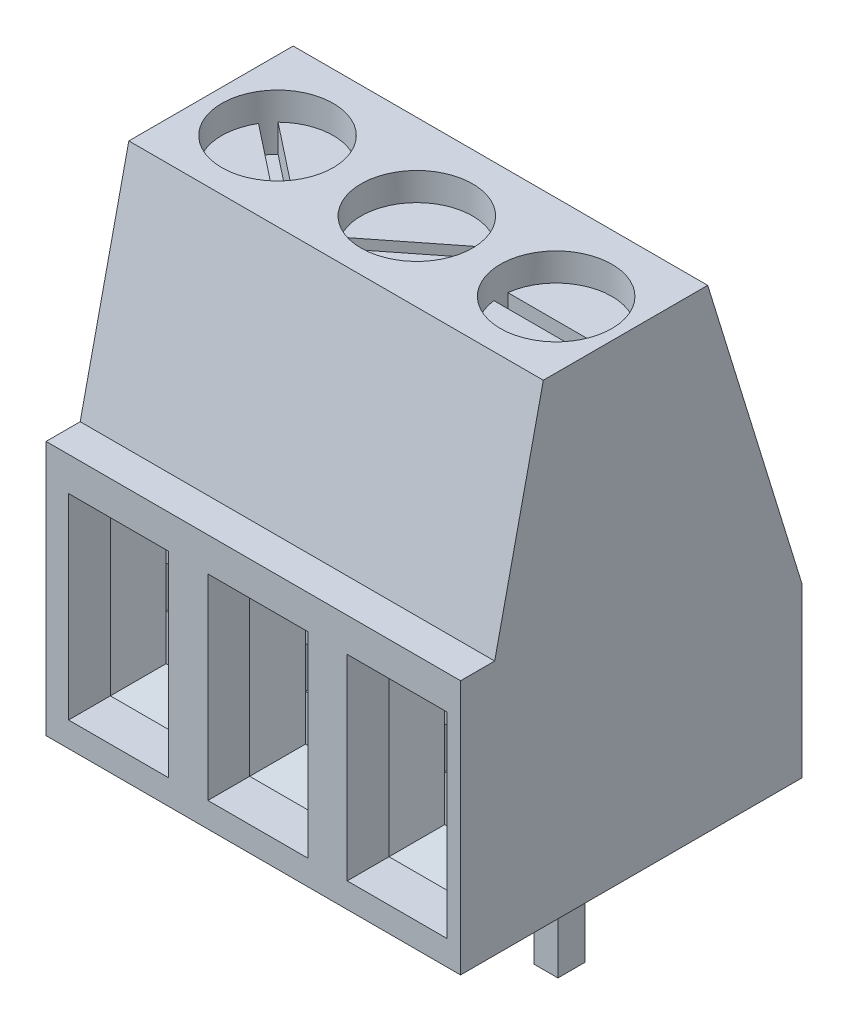
SolidWorks part; units mm, degrees
ref_plane "Front Plane" through (0, 0, 0) normal (0, 0, 1) x (1, 0, 0)
ref_plane "Top Plane" through (0, 0, 0) normal (0, 1, 0) x (1, 0, 0)
ref_plane "Right Plane" through (0, 0, 0) normal (1, 0, 0) x (0, 0, -1)
sketch "Sketch1" plane through (0, 0, 0) normal (0, 1, 0) x (1, 0, 0)
  line L1 (0, 0) -> (20.701, 0)
  line L2 (0, 0) -> (0, 6.223)
  line L3 (0, 6.223) -> (20.701, 6.223)
  line L4 (20.701, 0) -> (20.701, 6.223)
  dimension "D1" = 20.701
  dimension "D2" = 6.223
extrude "Extrude1" add sketch "Sketch1" along normal blind 8.636
sketch "Sketch2" plane through (20.701, 0, 0) normal (1, 0, 0) x (0, 0, -1)
  line L0 (-2.8691, 4.6459) -> (0.6218, 4.6459)
  line L1 (0.6218, 4.6459) -> (2.2176, 11.8272)
  line L2 (2.2176, 11.8272) -> (-2.8691, 11.8272)
  line L3 (-2.8691, 11.8272) -> (-2.8691, 4.6459)
extrude "Cut-Extrude1" cut sketch "Sketch2" against normal blind 25.4
sketch "Sketch3" plane through (20.701, 0, 0) normal (1, 0, 0) x (0, 0, -1)
  line L0 (4.013, 10.2314) -> (6.9054, 0.8558)
  line L1 (6.9054, 0.8558) -> (9.1994, 0.8558)
  line L2 (9.1994, 0.8558) -> (9.1994, 10.2314)
  line L3 (9.1994, 10.2314) -> (4.013, 10.2314)
extrude "Cut-Extrude2" cut sketch "Sketch3" against normal blind 25.4
sketch "Sketch4" plane through (0, 8.636, 0) normal (0, 1, 0) x (1, 0, 0)
  line L0 (0, 4.5051) -> (0, 1.5085) construction
  circle A0 centre (1.27, 2.9491) radius 1.016
  circle A1 centre (3.81, 2.9491) radius 1.016
  circle A2 centre (6.35, 2.9491) radius 1.016
  circle A3 centre (8.89, 2.9491) radius 1.016
  circle A4 centre (11.43, 2.9491) radius 1.016
  circle A5 centre (13.97, 2.9491) radius 1.016
  circle A6 centre (16.51, 2.9491) radius 1.016
  circle A7 centre (19.05, 2.9491) radius 1.016
  dimension "D1" = 1.27
extrude "Cut-Extrude3" cut sketch "Sketch4" against normal blind 0.508
sketch "Sketch5" plane through (0, 8.128, 0) normal (0, 1, 0) x (1, 0, 0)
  line L8 (18.1734, 3.4782) -> (19.7694, 2.2205)
  line L9 (16.7061, 3.9541) -> (16.0726, 2.0233)
  line L10 (12.9692, 3.1653) -> (14.8868, 2.4932)
  line L11 (11.303, 3.9651) -> (11.303, 1.9331)
  line L12 (8.6939, 1.9441) -> (9.3274, 3.8749)
  line L13 (5.334, 2.8221) -> (7.366, 2.8221)
  line L14 (3.0906, 2.2205) -> (4.6866, 3.4782)
  line L15 (0.3934, 3.4782) -> (1.9894, 2.2205)
  line L16 (18.3306, 3.6777) -> (19.9266, 2.42)
  line L17 (16.9474, 3.8749) -> (16.3139, 1.9441)
  line L18 (13.0532, 3.405) -> (14.9708, 2.7329)
  line L19 (11.557, 3.9651) -> (11.557, 1.9331)
  line L20 (8.4526, 2.0233) -> (9.0861, 3.9541)
  line L21 (5.334, 3.0761) -> (7.366, 3.0761)
  line L22 (2.9334, 2.42) -> (4.5294, 3.6777)
  line L23 (0.5506, 3.6777) -> (2.1466, 2.42)
  circle A13 centre (1.27, 2.9491) radius 1.016
  circle A14 centre (3.81, 2.9491) radius 1.016
  circle A15 centre (6.35, 2.9491) radius 1.016
  circle A16 centre (8.89, 2.9491) radius 1.005
  circle A17 centre (11.43, 2.9491) radius 1.016
  circle A18 centre (13.97, 2.9491) radius 1.016
  circle A19 centre (16.51, 2.9491) radius 1.016
  circle A20 centre (19.05, 2.9491) radius 0.9996
  circle M1 centre (1.27, 2.9491) radius 1.016
extrude "Cut-Extrude4" cut sketch "Sketch5" against normal blind 0.508 contours L23 L15 M1 | L14 A14 L22 | L13 A15 L21 | L12 A16 L20 | L19 A17 L11 | L10 A18 L18 | L17 A19 L9 | L8 A20 L16
sketch "Sketch6" plane through (0, 0, 0) normal (0, 0, 1) x (1, 0, 0)
  line L0 (2.9501, 4.0288) -> (2.9501, 0.4524)
  line L1 (0.4101, 4.0288) -> (2.232, 4.0288)
  line L2 (0.4101, 4.0288) -> (0.4101, 0.4524)
  line L3 (0.4101, 0.4524) -> (2.232, 0.4524)
  line L4 (2.232, 4.0288) -> (2.232, 0.4524)
  line L5 (2.9501, 4.0288) -> (4.772, 4.0288)
  line L6 (4.772, 4.0288) -> (4.772, 0.4524)
  line L7 (2.9501, 0.4524) -> (4.772, 0.4524)
  line L8 (5.4901, 4.0288) -> (5.4901, 0.4524)
  line L9 (5.4901, 4.0288) -> (7.312, 4.0288)
  line L10 (7.312, 4.0288) -> (7.312, 0.4524)
  line L11 (5.4901, 0.4524) -> (7.312, 0.4524)
  line L12 (8.0301, 4.0288) -> (8.0301, 0.4524)
  line L13 (8.0301, 4.0288) -> (9.852, 4.0288)
  line L14 (9.852, 4.0288) -> (9.852, 0.4524)
  line L15 (8.0301, 0.4524) -> (9.852, 0.4524)
  line L16 (10.5701, 4.0288) -> (10.5701, 0.4524)
  line L17 (10.5701, 4.0288) -> (12.392, 4.0288)
  line L18 (12.392, 4.0288) -> (12.392, 0.4524)
  line L19 (10.5701, 0.4524) -> (12.392, 0.4524)
  line L20 (13.1101, 4.0288) -> (13.1101, 0.4524)
  line L21 (13.1101, 4.0288) -> (14.932, 4.0288)
  line L22 (14.932, 4.0288) -> (14.932, 0.4524)
  line L23 (13.1101, 0.4524) -> (14.932, 0.4524)
  line L24 (15.6501, 4.0288) -> (15.6501, 0.4524)
  line L25 (15.6501, 4.0288) -> (17.472, 4.0288)
  line L26 (17.472, 4.0288) -> (17.472, 0.4524)
  line L27 (15.6501, 0.4524) -> (17.472, 0.4524)
  line L28 (18.1901, 4.0288) -> (18.1901, 0.4524)
  line L29 (18.1901, 4.0288) -> (20.012, 4.0288)
  line L30 (20.012, 4.0288) -> (20.012, 0.4524)
  line L31 (18.1901, 0.4524) -> (20.012, 0.4524)
extrude "Cut-Extrude5" cut sketch "Sketch6" against normal blind 1.27
chamfer "Chamfer1" distance 0.508 angle 45 11 edges at (7.312, 2.2406, -1.27) (5.4901, 2.2406, -1.27) (6.4011, 4.0288, -1.27) (4.772, 2.2406, -1.27) (3.8611, 0.4524, -1.27) (2.9501, 2.2406, -1.27) (3.8611, 4.0288, -1.27) (1.3211, 4.0288, -1.27) (2.232, 2.2406, -1.27) (1.3211, 0.4524, -1.27) (0.4101, 2.2406, -1.27)
sketch "Sketch7" plane through (0, 0, -1.27) normal (0, 0, 1) x (1, 0, 0)
  line L0 (0.9181, 3.5208) -> (0.9181, 0.9604) construction
  line L1 (0.9181, 2.5517) -> (1.724, 2.5517)
  line L2 (0.9181, 2.5517) -> (0.9181, 1.7937)
  line L3 (0.9181, 1.7937) -> (1.724, 1.7937)
  line L4 (1.724, 2.5517) -> (1.724, 1.7937)
  line L5 (1.724, 0.9604) -> (1.724, 3.5208) construction
  line L6 (3.4581, 2.5517) -> (3.4581, 1.7937)
  line L7 (3.4581, 2.5517) -> (4.264, 2.5517)
  line L8 (4.264, 2.5517) -> (4.264, 1.7937)
  line L9 (3.4581, 1.7937) -> (4.264, 1.7937)
  line L10 (5.9981, 2.5517) -> (5.9981, 1.7937)
  line L11 (5.9981, 2.5517) -> (6.804, 2.5517)
  line L12 (6.804, 2.5517) -> (6.804, 1.7937)
  line L13 (5.9981, 1.7937) -> (6.804, 1.7937)
  line L14 (8.5381, 2.5517) -> (8.5381, 1.7937)
  line L15 (8.5381, 2.5517) -> (9.344, 2.5517)
  line L16 (9.344, 2.5517) -> (9.344, 1.7937)
  line L17 (8.5381, 1.7937) -> (9.344, 1.7937)
  line L18 (11.0781, 2.5517) -> (11.0781, 1.7937)
  line L19 (11.0781, 2.5517) -> (11.884, 2.5517)
  line L20 (11.884, 2.5517) -> (11.884, 1.7937)
  line L21 (11.0781, 1.7937) -> (11.884, 1.7937)
  line L22 (13.6181, 2.5517) -> (13.6181, 1.7937)
  line L23 (13.6181, 2.5517) -> (14.424, 2.5517)
  line L24 (14.424, 2.5517) -> (14.424, 1.7937)
  line L25 (13.6181, 1.7937) -> (14.424, 1.7937)
  line L26 (16.1581, 2.5517) -> (16.1581, 1.7937)
  line L27 (16.1581, 2.5517) -> (16.964, 2.5517)
  line L28 (16.964, 2.5517) -> (16.964, 1.7937)
  line L29 (16.1581, 1.7937) -> (16.964, 1.7937)
  line L30 (18.6981, 2.5517) -> (18.6981, 1.7937)
  line L31 (18.6981, 2.5517) -> (19.504, 2.5517)
  line L32 (19.504, 2.5517) -> (19.504, 1.7937)
  line L33 (18.6981, 1.7937) -> (19.504, 1.7937)
extrude "Cut-Extrude6" cut sketch "Sketch7" against normal blind 1.27
sketch "Sketch8" plane through (0, 0, 0) normal (0, -1, 0) x (1, 0, 0)
  line L0 (3.6128, -2.7447) -> (3.6128, -3.2358)
  line L1 (1.0728, -2.7447) -> (1.5062, -2.7447)
  line L2 (1.0728, -2.7447) -> (1.0728, -3.2358)
  line L3 (1.0728, -3.2358) -> (1.5062, -3.2358)
  line L4 (1.5062, -2.7447) -> (1.5062, -3.2358)
  line L5 (3.6128, -2.7447) -> (4.0462, -2.7447)
  line L6 (4.0462, -2.7447) -> (4.0462, -3.2358)
  line L7 (3.6128, -3.2358) -> (4.0462, -3.2358)
  line L8 (6.1528, -2.7447) -> (6.1528, -3.2358)
  line L9 (6.1528, -2.7447) -> (6.5862, -2.7447)
  line L10 (6.5862, -2.7447) -> (6.5862, -3.2358)
  line L11 (6.1528, -3.2358) -> (6.5862, -3.2358)
  line L12 (8.6928, -2.7447) -> (8.6928, -3.2358)
  line L13 (8.6928, -2.7447) -> (9.1262, -2.7447)
  line L14 (9.1262, -2.7447) -> (9.1262, -3.2358)
  line L15 (8.6928, -3.2358) -> (9.1262, -3.2358)
  line L16 (11.2328, -2.7447) -> (11.2328, -3.2358)
  line L17 (11.2328, -2.7447) -> (11.6662, -2.7447)
  line L18 (11.6662, -2.7447) -> (11.6662, -3.2358)
  line L19 (11.2328, -3.2358) -> (11.6662, -3.2358)
  line L20 (13.7728, -2.7447) -> (13.7728, -3.2358)
  line L21 (13.7728, -2.7447) -> (14.2062, -2.7447)
  line L22 (14.2062, -2.7447) -> (14.2062, -3.2358)
  line L23 (13.7728, -3.2358) -> (14.2062, -3.2358)
  line L24 (16.3128, -2.7447) -> (16.3128, -3.2358)
  line L25 (16.3128, -2.7447) -> (16.7462, -2.7447)
  line L26 (16.7462, -2.7447) -> (16.7462, -3.2358)
  line L27 (16.3128, -3.2358) -> (16.7462, -3.2358)
  line L28 (18.8528, -2.7447) -> (18.8528, -3.2358)
  line L29 (18.8528, -2.7447) -> (19.2862, -2.7447)
  line L30 (19.2862, -2.7447) -> (19.2862, -3.2358)
  line L31 (18.8528, -3.2358) -> (19.2862, -3.2358)
extrude "Extrude2" add sketch "Sketch8" along normal blind 1.905
sketch "Sketch9" plane through (0, 8.636, 0) normal (0, 1, 0) x (1, 0, 0)
  line L1 (7.5567, 8.0072) -> (21.3925, 8.0072)
  line L2 (7.5567, 8.0072) -> (7.5567, -3.0614)
  line L3 (7.5567, -3.0614) -> (21.3925, -3.0614)
  line L4 (21.3925, 8.0072) -> (21.3925, -3.0614)
extrude "Cut-Extrude7" cut sketch "Sketch9" against normal blind 25.4
